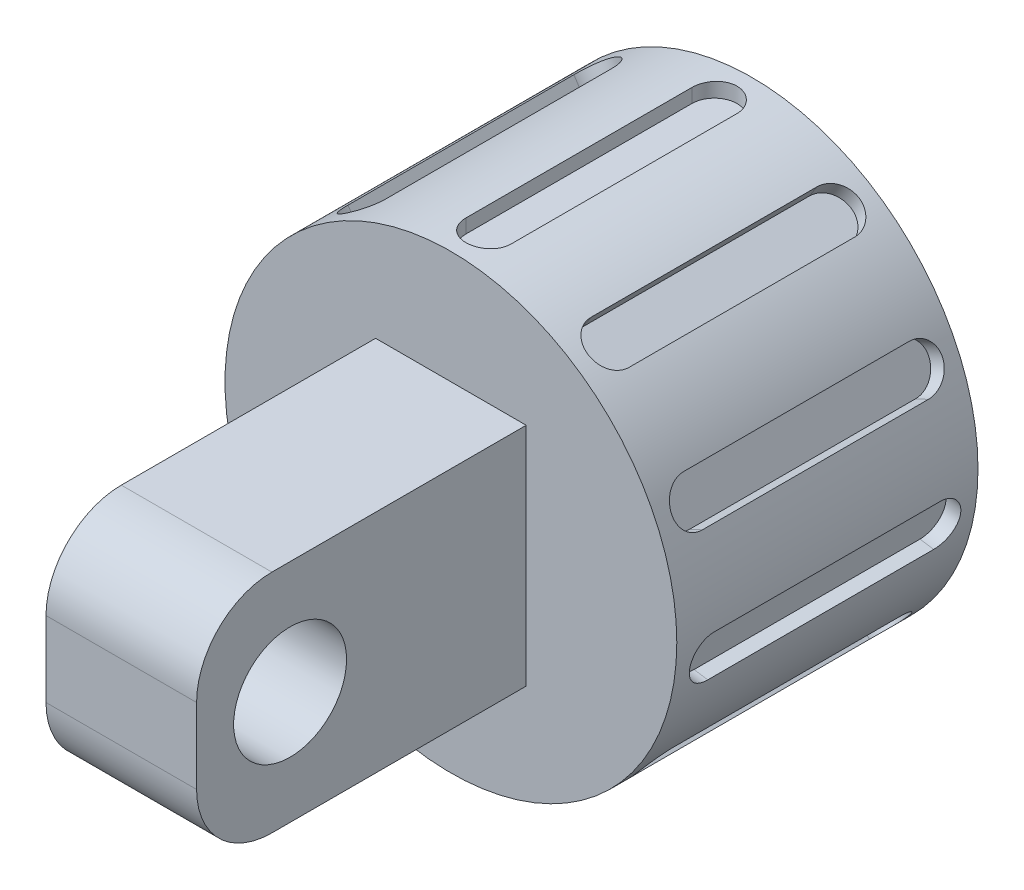
SolidWorks part; units mm, degrees
ref_plane "Front Plane" through (0, 0, 0) normal (0, 0, 1) x (1, 0, 0)
ref_plane "Top Plane" through (0, 0, 0) normal (0, 1, 0) x (1, 0, 0)
ref_plane "Right Plane" through (0, 0, 0) normal (1, 0, 0) x (0, 0, -1)
sketch "Sketch1" plane through (0, 0, 0) normal (0, 0, 1) x (1, 0, 0)
  circle A0 centre (0, 0) radius 30
  dimension "D1" = 60
extrude "Boss-Extrude1" add sketch "Sketch1" along normal mid plane 40
sketch "Sketch2" plane through (0, 0, 0) normal (1, 0, 0) x (0, 0, -1)
  line L0 (0, 0) -> (-63.7729, 0) construction
  line L1 (-20, -15) -> (-20, 15)
  line L2 (-20, 30) -> (-20, -30) construction
  line L4 (-20, 15) -> (-63.7729, 15)
  line L5 (-20, 15) -> (-20, -15)
  line L6 (-20, -15) -> (-63.7729, -15)
  line L7 (-63.7729, 15) -> (-63.7729, -15)
  line L8 (-41.8865, -15) -> (-41.8865, 15) construction
  line L9 (-20, 0) -> (-63.7729, 0) construction
  point P12 (-20, 0)
  point P206 (-41.8865, 0)
  dimension "D1" = 15
extrude "Boss-Extrude2" add sketch "Sketch2" along normal mid plane 20 contours L4 L7 L6 L1
fillet "Fillet1" radius 10 2 edges at (0, -15, 63.7729) (0, 15, 63.7729)
sketch "Sketch3" plane through (10, 0, 0) normal (1, 0, 0) x (0, 0, -1)
  line L0 (-63.7729, 0) -> (-38.9415, 0) construction
  line L1 (-63.7729, 5) -> (-63.7729, -5) construction
  circle A0 centre (-51.3572, 0) radius 7.5
  dimension "D1" = 15
extrude "Cut-Extrude1" cut sketch "Sketch3" against normal through all both and the other way through all
sketch "Sketch4" plane through (0, 0, 0) normal (0, 1, 0) x (1, 0, 0)
  line L0 (0, 15) -> (0, -15) construction
  line L1 (3, 15) -> (3, -15)
  line L2 (-3, 15) -> (-3, -15)
  arc A0 (3, 15) -> (-3, 15) centre (0, 15) ccw
  arc A1 (-3, -15) -> (3, -15) centre (0, -15) ccw
  point P2 (0, 0)
  dimension "D2" = 3
  dimension "D1" = 30
extrude "Cut-Extrude2" cut sketch "Sketch4" along normal blind 20 from offset 28
pattern_circular "CirPattern1" count 11 over 360 about axis through (0, 0, 0) along (0, 0, 1) of "Cut-Extrude2"
sketch "Sketch5" plane through (0, 0, -20) normal (0, 0, -1) x (-1, 0, 0)
  circle A0 centre (0, 0) radius 15
  dimension "D1" = 30
extrude "Cut-Extrude3" cut sketch "Sketch5" against normal blind 11.5
